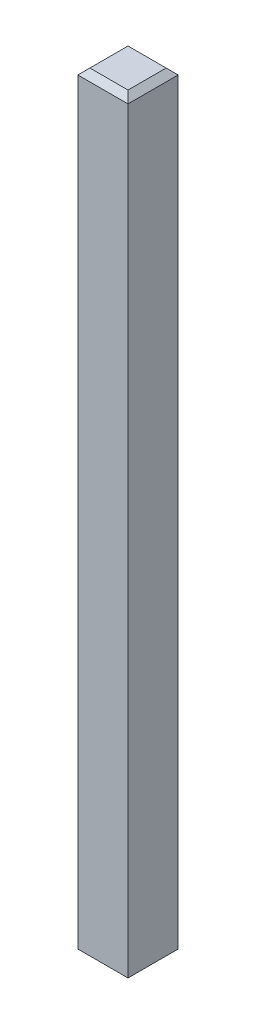
SolidWorks part; units mm, degrees
ref_plane "Front Plane" through (0, 0, 0) normal (0, 0, 1) x (1, 0, 0)
ref_plane "Top Plane" through (0, 0, 0) normal (0, 1, 0) x (1, 0, 0)
ref_plane "Right Plane" through (0, 0, 0) normal (1, 0, 0) x (0, 0, -1)
sketch "Sketch1" plane through (0, 0, 0) normal (0, 1, 0) x (1, 0, 0)
  line L1 (-0.375, 0.375) -> (0.375, 0.375)
  line L2 (-0.375, 0.375) -> (-0.375, -0.375)
  line L3 (-0.375, -0.375) -> (0.375, -0.375)
  line L4 (0.375, 0.375) -> (0.375, -0.375)
  line L5 (-0.375, 0.375) -> (0.375, -0.375) construction
  line L6 (-0.375, -0.375) -> (0.375, 0.375) construction
  point P0 (0, 0)
  dimension "D1" = 0.75
  dimension "D2" = 0.75
extrude "Boss-Extrude1" add sketch "Sketch1" along normal blind 11.5
chamfer "Chamfer1" distance 0.09 angle 45 8 edges at (0, 0, -0.375) (-0.375, 0, 0) (0, 0, 0.375) (0.375, 0, 0) (0, 11.5, 0.375) (-0.375, 11.5, 0) (0, 11.5, -0.375) (0.375, 11.5, 0)
